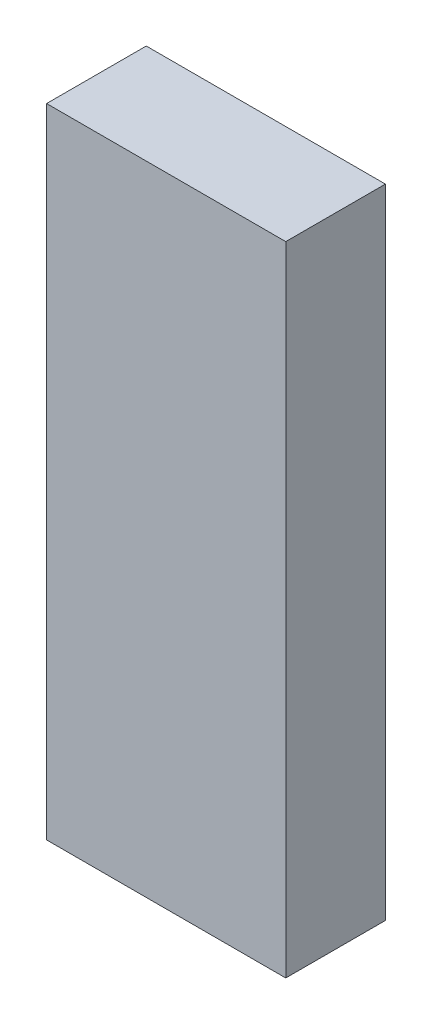
SolidWorks part; units mm, degrees
ref_plane "Front Plane" through (0, 0, 0) normal (0, 0, 1) x (1, 0, 0)
ref_plane "Top Plane" through (0, 0, 0) normal (0, 1, 0) x (1, 0, 0)
ref_plane "Right Plane" through (0, 0, 0) normal (1, 0, 0) x (0, 0, -1)
sketch "Sketch1" plane through (0, 0, 0) normal (0, 0, 1) x (1, 0, 0)
  line L1 (-9.525, 25.4) -> (9.525, 25.4)
  line L2 (-9.525, 25.4) -> (-9.525, -25.4)
  line L3 (-9.525, -25.4) -> (9.525, -25.4)
  line L4 (9.525, 25.4) -> (9.525, -25.4)
  line L5 (-9.525, 25.4) -> (9.525, -25.4) construction
  line L6 (-9.525, -25.4) -> (9.525, 25.4) construction
  point P0 (0, 0)
  dimension "D1" = 19.05
  dimension "D2" = 50.8
extrude "Boss-Extrude1" add sketch "Sketch1" along normal blind 7.9375
